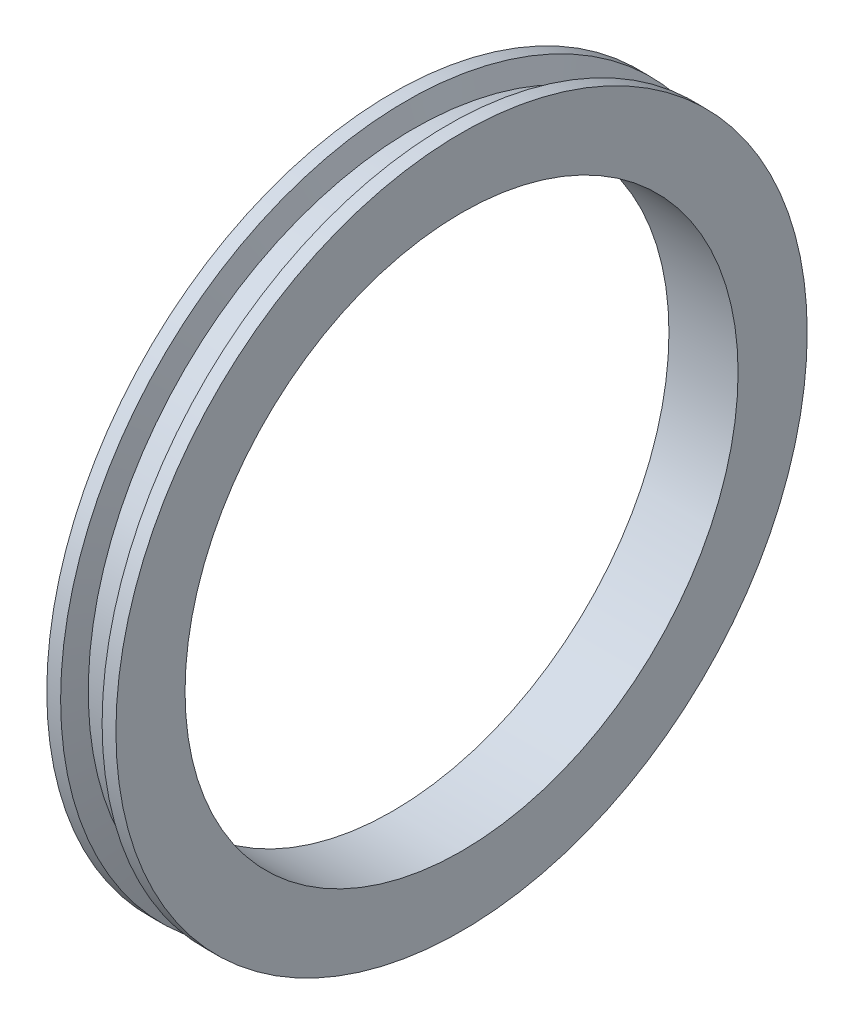
SolidWorks part; units mm, degrees
ref_plane "Front Plane" through (0, 0, 0) normal (0, 0, 1) x (1, 0, 0)
ref_plane "Top Plane" through (0, 0, 0) normal (0, 1, 0) x (1, 0, 0)
ref_plane "Right Plane" through (0, 0, 0) normal (1, 0, 0) x (0, 0, -1)
sketch "Sketch1" plane through (0, 0, 0) normal (0, 0, 1) x (1, 0, 0)
  line L0 (0, 0) -> (0, 50)
  line L1 (0, 50) -> (2, 50)
  line L2 (2, 50) -> (3, 47)
  line L3 (3, 47) -> (7, 47)
  line L4 (7, 47) -> (8, 50)
  line L5 (8, 50) -> (10, 50)
  line L6 (10, 50) -> (10, 0)
  line L7 (10, 0) -> (0, 0)
  dimension "D1" = 50
  dimension "D2" = 50
  dimension "D3" = 2
  dimension "D4" = 2
  dimension "D5" = 1
  dimension "D6" = 1
  dimension "D7" = 4
  dimension "D8" = 47
revolve "Revolve1" add sketch "Sketch1" angle 360 about L7
sketch "Sketch2" plane through (10, 0, 0) normal (1, 0, 0) x (0, 0, -1)
  circle A0 centre (0, 0) radius 40
  dimension "D1" = 80
extrude "Cut-Extrude1" cut sketch "Sketch2" against normal blind 10
